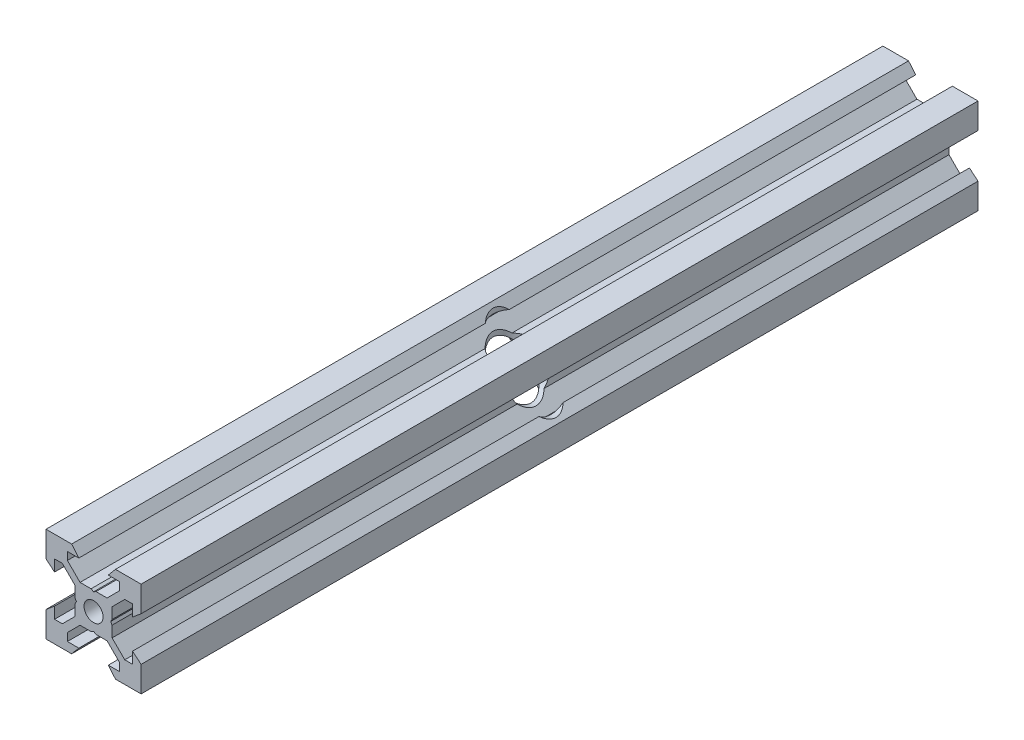
SolidWorks part; units mm, degrees
material "3.3535 (EN-AW 5754)"
ref_plane "Front Plane" through (0, 0, 0) normal (0, 0, 1) x (1, 0, 0)
ref_plane "Top Plane" through (0, 0, 0) normal (0, 1, 0) x (1, 0, 0)
ref_plane "Right Plane" through (0, 0, 0) normal (1, 0, 0) x (0, 0, -1)
sketch "Sketch1" plane through (0, 0, 0) normal (0, 0, 1) x (1, 0, 0)
  line L0 (10, 10) -> (4.6104, 10) construction
  line L1 (10, 10) -> (10, 4.6104) construction
  line L2 (10, -10) -> (10, -4.6104) construction
  line L3 (10, -10) -> (4.6104, -10) construction
  line L4 (10, 10) -> (10, 4.6104)
  line L5 (6.5607, 5.5) -> (8.2, 5.5)
  line L6 (5.5, 8.2) -> (5.5, 6.5607)
  line L7 (10, 10) -> (4.6104, 10)
  line L8 (10, 10) -> (10, 4.6104)
  line L9 (6.5607, 5.5) -> (3.9, 2.8393)
  line L10 (5.5, 6.5607) -> (2.8393, 3.9)
  line L11 (10, 4.6104) -> (8.2, 3.1)
  line L12 (4.6104, 10) -> (3.1, 8.2)
  line L13 (8.2, 3.1) -> (8.2, 5.5)
  line L14 (3.1, 8.2) -> (5.5, 8.2)
  line L15 (-6.5607, 5.5) -> (-8.2, 5.5)
  line L16 (6.5607, -5.5) -> (8.2, -5.5)
  line L17 (3.1, -8.2) -> (5.5, -8.2)
  line L18 (8.2, -3.1) -> (8.2, -5.5)
  line L19 (4.6104, -10) -> (3.1, -8.2)
  line L20 (10, -4.6104) -> (8.2, -3.1)
  line L21 (0.5196, -3.9) -> (0, -3.6)
  line L22 (0.5196, 3.9) -> (0, 3.6)
  line L23 (3.6, 0) -> (3.9, -0.5196)
  line L24 (3.9, 0.5196) -> (3.6, 0)
  line L25 (3.9, 0.5196) -> (3.9, 2.8393)
  line L26 (2.8393, 3.9) -> (0.5196, 3.9)
  line L27 (3.9, -2.8393) -> (3.9, -0.5196)
  line L28 (2.8393, -3.9) -> (0.5196, -3.9)
  line L29 (5.5, -6.5607) -> (2.8393, -3.9)
  line L30 (6.5607, -5.5) -> (3.9, -2.8393)
  line L31 (10, -10) -> (10, -4.6104)
  line L32 (10, -10) -> (4.6104, -10)
  line L33 (5.5, -8.2) -> (5.5, -6.5607)
  line L34 (-6.5607, -5.5) -> (-8.2, -5.5)
  line L35 (10, -10) -> (10, -4.6104)
  line L36 (0, 0) -> (0, 8.2) construction
  line L37 (-10, -10) -> (-4.6104, -10) construction
  line L38 (-10, -10) -> (-10, -4.6104) construction
  line L39 (-10, 10) -> (-10, 4.6104) construction
  line L40 (-10, 10) -> (-4.6104, 10) construction
  line L41 (-10, -10) -> (-10, -4.6104)
  line L43 (-5.5, -8.2) -> (-5.5, -6.5607)
  line L44 (-10, -10) -> (-4.6104, -10)
  line L45 (-10, -10) -> (-10, -4.6104)
  line L46 (-6.5607, -5.5) -> (-3.9, -2.8393)
  line L47 (-5.5, -6.5607) -> (-2.8393, -3.9)
  line L48 (-2.8393, -3.9) -> (-0.5196, -3.9)
  line L49 (-3.9, -2.8393) -> (-3.9, -0.5196)
  line L50 (-2.8393, 3.9) -> (-0.5196, 3.9)
  line L51 (-3.9, 0.5196) -> (-3.9, 2.8393)
  line L52 (-3.9, 0.5196) -> (-3.6, 0)
  line L53 (-3.6, 0) -> (-3.9, -0.5196)
  line L54 (-0.5196, 3.9) -> (0, 3.6)
  line L55 (-0.5196, -3.9) -> (0, -3.6)
  line L56 (-10, -4.6104) -> (-8.2, -3.1)
  line L57 (-4.6104, -10) -> (-3.1, -8.2)
  line L58 (-8.2, -3.1) -> (-8.2, -5.5)
  line L59 (-3.1, -8.2) -> (-5.5, -8.2)
  line L60 (-10, -10) -> (10, -10) construction
  line L61 (-10, -10) -> (-10, 10) construction
  line L62 (-3.1, 8.2) -> (-5.5, 8.2)
  line L63 (-8.2, 3.1) -> (-8.2, 5.5)
  line L64 (-4.6104, 10) -> (-3.1, 8.2)
  line L65 (-10, 4.6104) -> (-8.2, 3.1)
  line L66 (-5.5, 6.5607) -> (-2.8393, 3.9)
  line L67 (-6.5607, 5.5) -> (-3.9, 2.8393)
  line L68 (-10, 10) -> (-10, 4.6104)
  line L69 (-10, 10) -> (-4.6104, 10)
  line L70 (-5.5, 8.2) -> (-5.5, 6.5607)
  line L71 (-10, 10) -> (10, 10) construction
  line L72 (-10, 10) -> (-10, 4.6104)
  line L73 (10, -10) -> (10, 10) construction
  line L74 (-10, -10) -> (10, 10) construction
  line L75 (-10, 10) -> (10, -10) construction
  circle A0 centre (0, 0) radius 2
  dimension "D7" = 4
  dimension "D1" = 20
  dimension "D2" = 5.3896
  dimension "D3" = 4.5
  dimension "D4" = 50
  dimension "D5" = 1.8
  dimension "D6" = 1.5104
  dimension "D8" = 5.5
  dimension "D9" = 120
  dimension "D10" = 0.3
  dimension "D11" = 2.3197
  dimension "D12" = 7.8
  dimension "D13" = 7.8
  dimension "D14" = 1.5
  dimension "D15" = 2.6607
extrude "Boss-Extrude1" add sketch "Sketch1" along normal blind 176 contours L70 L62 L64 L69 L68 L65 L63 L15 L67 L51 L52 L53 L49 L46 L34 L58 L56 L41 L44 L57 L59 L43 L47 L48 L55 L21 L28 L29 L33 L17 L19 L32 L31 L20 L18 L16 L30 L27 L23 L24 L25 L9 L5 L13 L11 L4 L7 L12 L14 L6 L10
sketch "Sketch4" plane through (0, 0, 0) normal (1, 0, 0) x (0, 0, -1)
  line L0 (-176, 0) -> (0, 0) construction
  circle A0 centre (-88, 0) radius 4
  dimension "D1" = 8
extrude "Cut-Extrude1" cut sketch "Sketch4" against normal through all both and the other way through all
sketch "Sketch5" plane through (0, 0, 0) normal (0, 1, 0) x (1, 0, 0)
  line L0 (0, 0) -> (0, -176) construction
  circle A0 centre (0, -88) radius 4
  dimension "D1" = 8
extrude "Cut-Extrude2" cut sketch "Sketch5" against normal through all both and the other way through all
